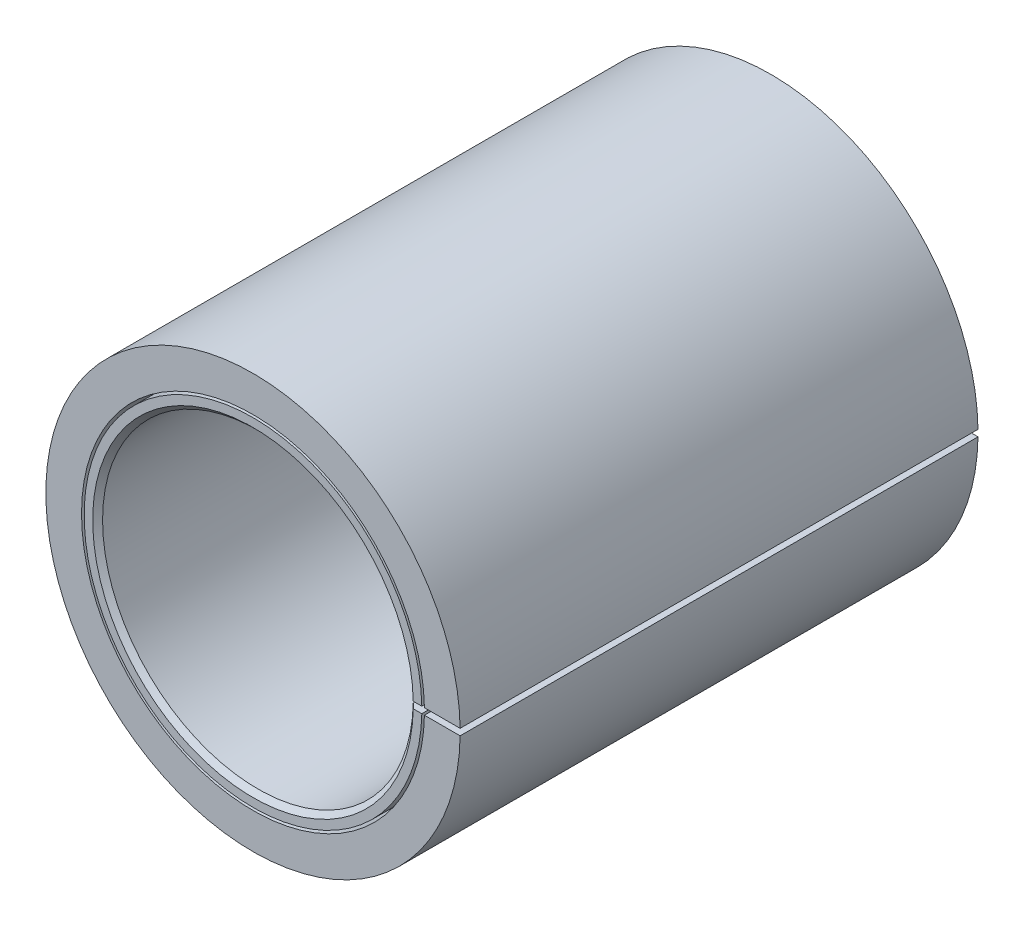
SolidWorks part; units mm, degrees
ref_plane "Front Plane" through (0, 0, 0) normal (0, 0, 1) x (1, 0, 0)
ref_plane "Top Plane" through (0, 0, 0) normal (0, 1, 0) x (1, 0, 0)
ref_plane "Right Plane" through (0, 0, 0) normal (1, 0, 0) x (0, 0, -1)
sketch "Sketch1" plane through (0, 0, 0) normal (0, 0, 1) x (1, 0, 0)
  line L0 (0, 4) -> (0, 3) construction
  line L1 (0, -3) -> (0, -4) construction
  line L2 (-3, 0) -> (-4, 0) construction
  circle A0 centre (0, 0) radius 3
  circle A1 centre (0, 0) radius 4
  circle A2 centre (0, 0) radius 3.2857 construction
  point P6 (0, 3.2857)
  dimension "ID" = 6
  dimension "OD" = 8
  dimension "D3" = 1
  dimension "D4" = 0.2857
  dimension "D1" = 1
extrude "Boss-Extrude1" add sketch "Sketch1" along normal mid plane 10
sketch "Sketch2" plane through (0, 0, 0) normal (0, 0, 1) x (1, 0, 0)
  circle A0 centre (0, 0) radius 3.2857 construction
  circle A1 centre (0, 0) radius 3.2857
extrude "Cut-Extrude-Thin1" cut sketch "Sketch2" against normal through all and the other way through all thin thin type mid plane wall 0.0508
chamfer "Chamfer1" distance 0.0952 angle 45 2 edges at (3, 0, 5) (3, 0, -5)
sketch "Sketch3" plane through (0, 0, 0) normal (1, 0, 0) x (0, 0, -1)
  line L0 (-5, 3) -> (5, 3)
  line L1 (-5, 4) -> (-5, -4) construction
  line L2 (5, -4) -> (5, 4) construction
  line L3 (-5, -3) -> (5, -3)
sketch "Sketch4" plane through (0, 0, 5) normal (0, 0, 1) x (1, 0, 0)
  line L0 (0, 0) -> (4, 0)
  circle A0 centre (0, 0) radius 4 construction
extrude "Cut-Extrude-Thin5" cut sketch "Sketch4" against normal through all thin thin type mid plane wall 0.125
equation "\"D4@Sketch1\" = \"D3@Sketch1\"/3.5"
equation "\"D1@Chamfer1\" = \"D4@Sketch1\"/3"
equation "\"D5@Cut-Extrude-Thin5\" = \"D1@Sketch1\"/8"
